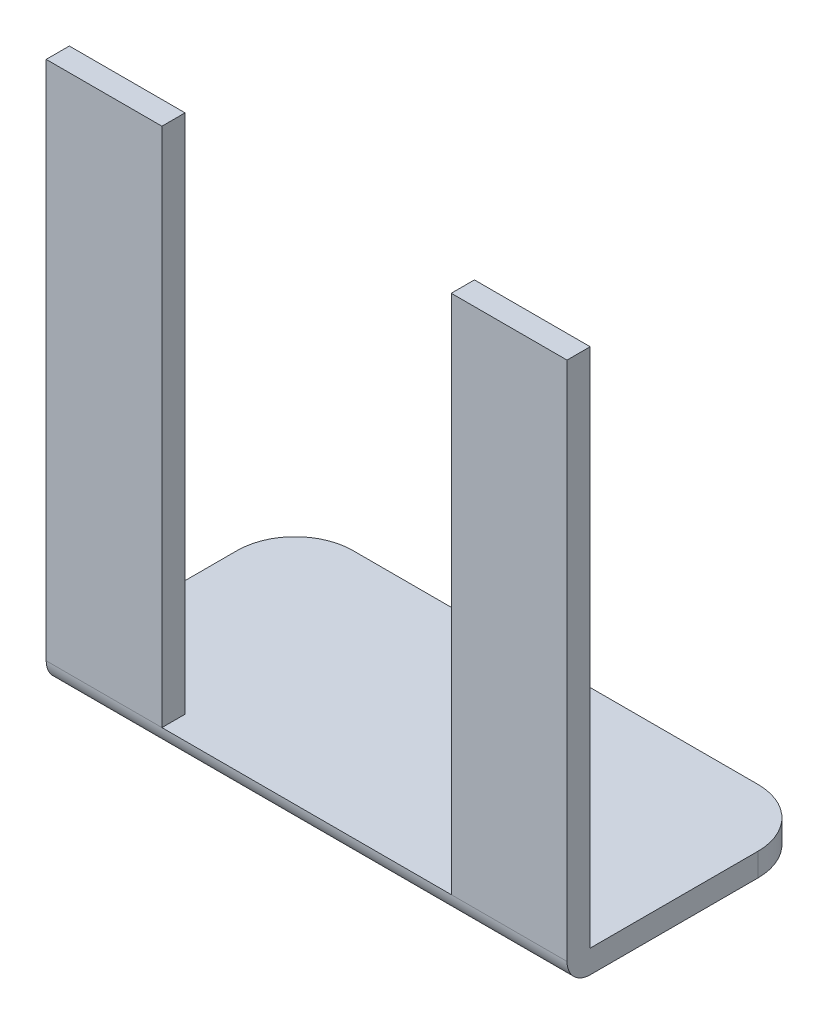
SolidWorks part; units mm, degrees
ref_plane "Front Plane" through (0, 0, 0) normal (0, 0, 1) x (1, 0, 0)
ref_plane "Top Plane" through (0, 0, 0) normal (0, 1, 0) x (1, 0, 0)
ref_plane "Right Plane" through (0, 0, 0) normal (1, 0, 0) x (0, 0, -1)
sketch "Sketch1" plane through (0, 0, 0) normal (0, 0, 1) x (1, 0, 0)
  line L1 (-22.5, 23.5) -> (22.5, 23.5)
  line L2 (-22.5, 23.5) -> (-22.5, -23.5)
  line L3 (-22.5, -23.5) -> (22.5, -23.5)
  line L4 (22.5, 23.5) -> (22.5, -23.5)
  line L5 (-22.5, 23.5) -> (22.5, -23.5) construction
  line L6 (-22.5, -23.5) -> (22.5, 23.5) construction
  point P0 (0, 0)
  dimension "D1" = 45
  dimension "D2" = 47
extrude "Boss-Extrude1" add sketch "Sketch1" along normal blind 2 contours L1 L4 L3 L2
sketch "Sketch2" plane through (0, 0, 0) normal (0, 0, -1) x (-1, 0, 0)
  line L0 (22.5, 23.5) -> (22.5, -23.5) construction
  line L1 (-22.5, -23.5) -> (22.5, -23.5)
  line L2 (-22.5, -23.5) -> (-22.5, -21.5)
  line L3 (-22.5, -21.5) -> (22.5, -21.5)
  line L4 (22.5, -23.5) -> (22.5, -21.5)
  dimension "D1" = 2
extrude "Boss-Extrude2" add sketch "Sketch2" along normal blind 19.5
fillet "Fillet1" radius 2 1 edges at (0, -23.5, 2)
fillet "Fillet2" radius 5 2 edges at (-22.5, -22.5, -19.5) (22.5, -22.5, -19.5)
sketch "Sketch3" plane through (0, 0, 2) normal (0, 0, 1) x (1, 0, 0)
  line L0 (-22.5, 23.5) -> (22.5, 23.5) construction
  line L1 (-12.5, 23.5) -> (12.5, 23.5)
  line L2 (-12.5, 23.5) -> (-12.5, 1)
  line L3 (-12.5, 1) -> (12.5, 1)
  line L4 (12.5, 23.5) -> (12.5, 1)
  point P6 (0, 23.5)
  dimension "D1" = 25
  dimension "D2" = 22.5
extrude "Cut-Extrude1" cut sketch "Sketch3" against normal through all contours L2 L3 L4 L1
sketch "Sketch4" plane through (0, -21.5, 0) normal (0, 1, 0) x (1, 0, 0)
  line L0 (-17.5, 19.5) -> (17.5, 19.5) construction
  circle A0 centre (0, 14.5) radius 1.5
  dimension "D1" = 3
  dimension "D2" = 5
extrude "Cut-Extrude2" cut sketch "Sketch4" against normal through all
sketch "Sketch5" plane through (0, 0, 0) normal (0, 0, -1) x (-1, 0, 0)
  line L0 (22.5, -21.5) -> (-22.5, -21.5) construction
  line L1 (-12.5, 1) -> (12.5, 1)
  line L2 (-12.5, 1) -> (-12.5, -21.5)
  line L3 (-12.5, -21.5) -> (12.5, -21.5)
  line L4 (12.5, 1) -> (12.5, -21.5)
  line L5 (12.5, 23.5) -> (12.5, 1) construction
extrude "Cut-Extrude3" cut sketch "Sketch5" against normal blind 10
equation "\"19.5.00mm\"=2"
